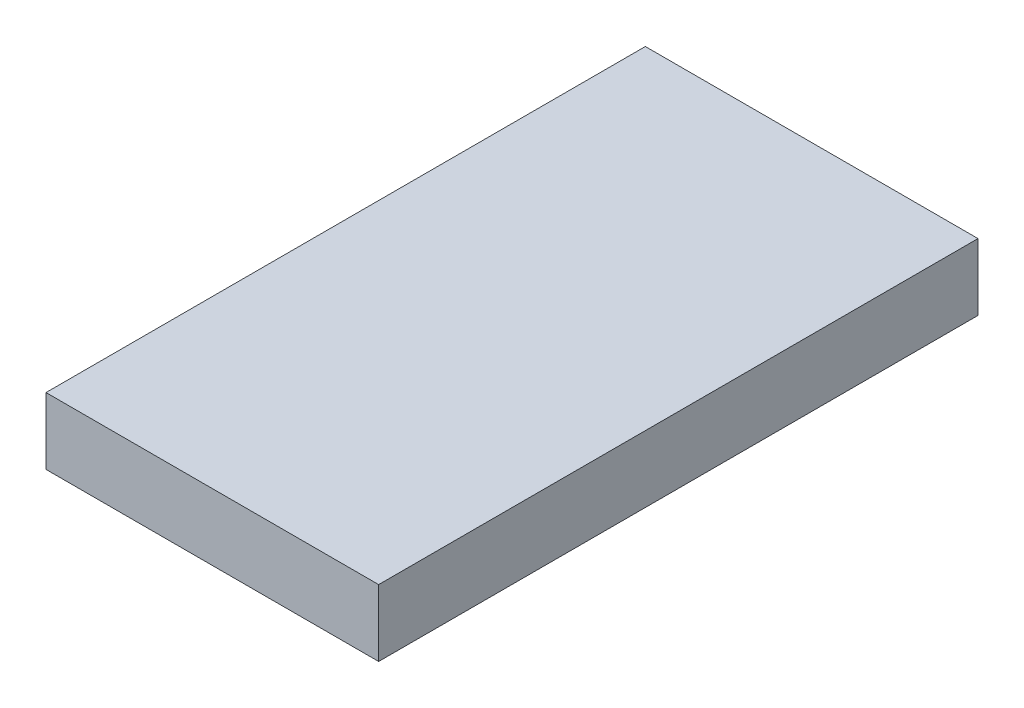
SolidWorks part; units mm, degrees
material "Custom Plastic"
ref_plane "X-Y Datum" through (0, 0, 0) normal (0, 0, 1) x (1, 0, 0)
ref_plane "X-Z Datum" through (0, 0, 0) normal (0, 1, 0) x (1, 0, 0)
ref_plane "Y-Z Datum" through (0, 0, 0) normal (1, 0, 0) x (0, 0, -1)
sketch "Sketch1" plane through (0, 0, 0) normal (0, 0, 1) x (1, 0, 0)
  line L1 (-63.4378, -12.7) -> (63.4378, -12.7)
  line L2 (-63.4378, -12.7) -> (-63.4378, 12.7)
  line L3 (-63.4378, 12.7) -> (63.4378, 12.7)
  line L4 (63.4378, -12.7) -> (63.4378, 12.7)
  line L5 (-63.4378, -12.7) -> (63.4378, 12.7) construction
  line L6 (-63.4378, 12.7) -> (63.4378, -12.7) construction
  point P0 (0, 0)
  dimension "D1" = 126.8755
  dimension "D2" = 25.4
extrude "Boss-Extrude1" add sketch "Sketch1" along normal blind 228.6
